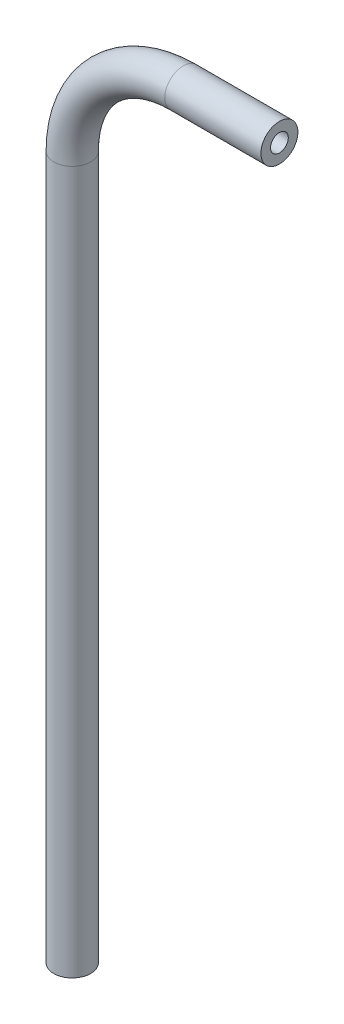
SolidWorks part; units mm, degrees
material "AISI Type 316L stainless steel"
ref_plane "Front Plane" through (0, 0, 0) normal (0, 0, 1) x (1, 0, 0)
ref_plane "Top Plane" through (0, 0, 0) normal (0, 1, 0) x (1, 0, 0)
ref_plane "Right Plane" through (0, 0, 0) normal (1, 0, 0) x (0, 0, -1)
sketch "Sketch1" plane through (0, 0, 0) normal (0, 0, 1) x (1, 0, 0)
  line L0 (0, -122.1723) -> (0, -1.5223)
  line L1 (19.05, 17.5277) -> (35.56, 17.5277)
  arc A0 (0, -1.5223) -> (19.05, 17.5277) centre (19.05, -1.5223) cw
  point P6 (0, 17.5277)
  dimension "D3" = 19.05
  dimension "D1" = 35.56
  dimension "D2" = 139.7
  dimension "D4" = 90
ref_plane "Plane1" through (35.56, 17.5277, 0) normal (1, 0, 0) x (0, 0, -1)
sketch "Sketch2" plane through (35.56, 17.5277, 0) normal (1, 0, 0) x (0, 0, -1)
  circle A0 centre (0, 0) radius 3.175
  circle A1 centre (0, 0) radius 1.524
  dimension "D1" = 6.35
  dimension "D2" = 3.048
sweep "Sweep1" add profiles "Sketch2" path "Sketch1"
